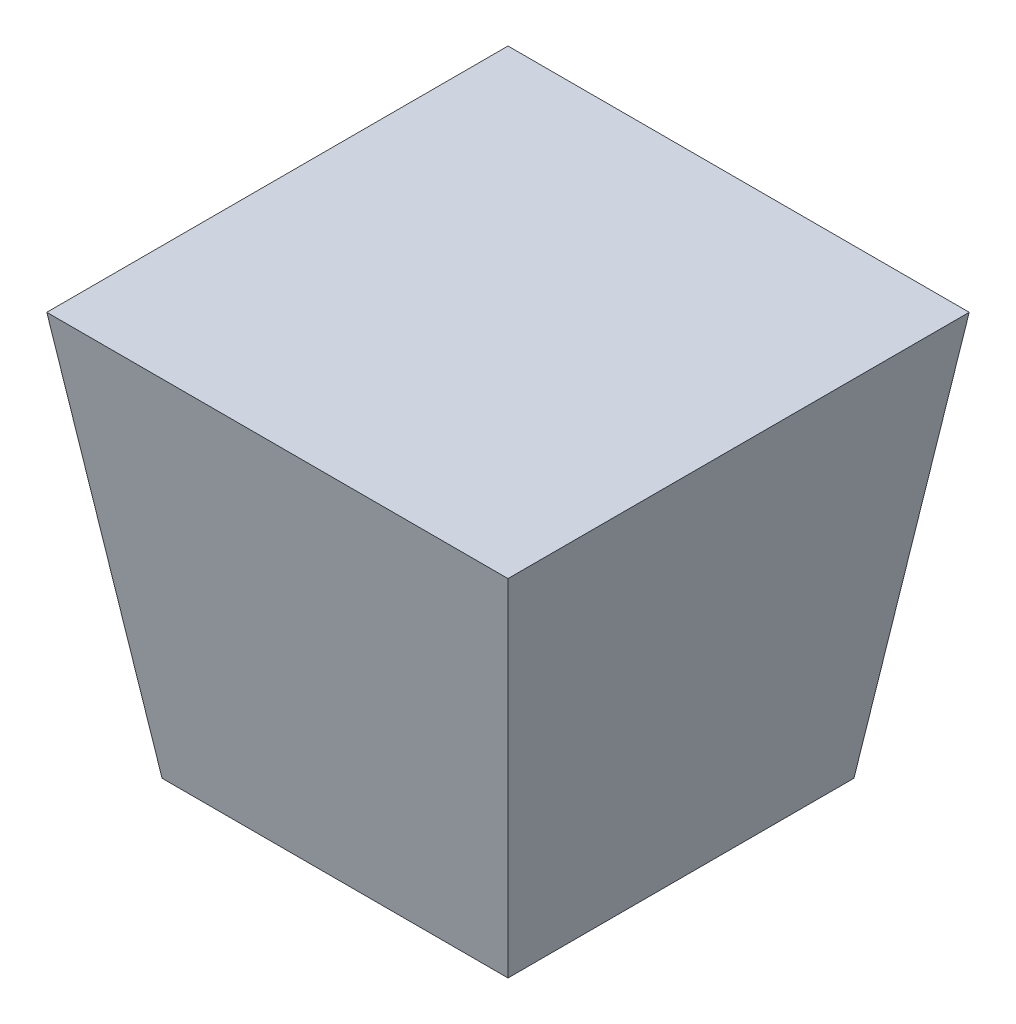
SolidWorks part; units mm, degrees
ref_plane "Спереди" through (0, 0, 0) normal (0, 0, 1) x (1, 0, 0)
ref_plane "Сверху" through (0, 0, 0) normal (0, 1, 0) x (1, 0, 0)
ref_plane "Справа" through (0, 0, 0) normal (1, 0, 0) x (0, 0, -1)
sketch "Эскиз1" plane through (0, 0, 0) normal (0, 1, 0) x (1, 0, 0)
  line L1 (-50.8078, 15.5432) -> (-10.8078, 15.5432)
  line L2 (-50.8078, 15.5432) -> (-50.8078, -24.4568)
  line L3 (-50.8078, -24.4568) -> (-10.8078, -24.4568)
  line L4 (-10.8078, 15.5432) -> (-10.8078, -24.4568)
  dimension "D1" = 40
  dimension "D2" = 40
extrude "Бобышка-Вытянуть1" add sketch "Эскиз1" along normal blind 40
sketch "Эскиз2" plane through (0, 0, -15.5432) normal (0, 0, -1) x (-1, 0, 0)
  line L0 (10.8078, 40) -> (10.8078, 0)
  line L1 (10.8078, 0) -> (20.8078, 0)
  line L2 (10.8078, 0) -> (50.8078, 0) construction
  line L3 (20.8078, 0) -> (10.8078, 40)
  dimension "D1" = 10
extrude "Вырез-Вытянуть1" cut sketch "Эскиз2" against normal through all
sketch "Эскиз3" plane through (-50.8078, 0, 0) normal (-1, 0, 0) x (0, 0, 1)
  line L0 (24.4568, 0) -> (14.4568, 0)
  line L1 (-15.5432, 0) -> (24.4568, 0) construction
  line L2 (14.4568, 0) -> (24.4568, 40)
  line L3 (24.4568, 40) -> (24.4568, 0)
  dimension "D1" = 10
extrude "Вырез-Вытянуть2" cut sketch "Эскиз3" against normal through all
